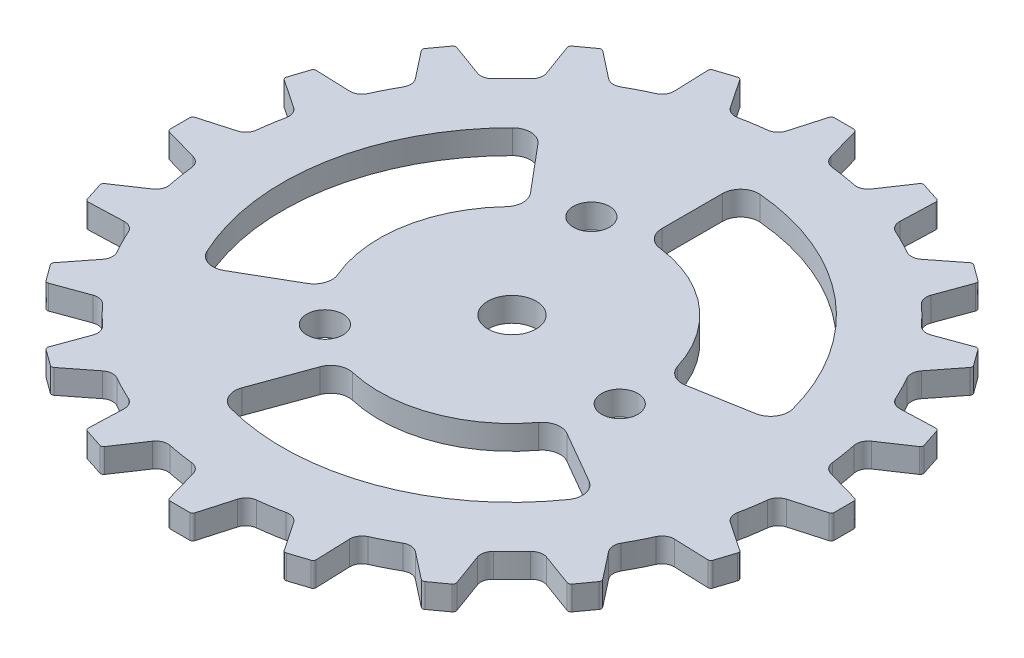
SolidWorks part; units mm, degrees
ref_plane "Front" through (0, 0, 0) normal (0, 0, 1) x (1, 0, 0)
ref_plane "Top" through (0, 0, 0) normal (0, 1, 0) x (1, 0, 0)
ref_plane "Right" through (0, 0, 0) normal (1, 0, 0) x (0, 0, -1)
sketch "草图1" plane through (0, 0, 0) normal (0, 1, 0) x (1, 0, 0)
  line L0 (-0.8114, 27.5) -> (0.8114, 27.5)
  line L3 (1.8377, 24.5681) -> (1.0518, 27.3187)
  line L7 (-1.8377, 24.5681) -> (-1.0518, 27.3187)
  line L8 (7.7263, 26.4048) -> (9.2697, 25.9033)
  line L9 (9.3397, 22.7977) -> (9.4423, 25.6566)
  line L10 (5.8442, 23.9335) -> (7.4416, 26.3066)
  line L11 (15.5076, 22.7249) -> (16.8206, 21.771)
  line L12 (15.9275, 18.7958) -> (16.9084, 21.483)
  line L13 (12.954, 20.9562) -> (15.2066, 22.7195)
  line L14 (21.771, 16.8206) -> (22.7249, 15.5076)
  line L15 (20.9562, 12.954) -> (22.7195, 15.2066)
  line L16 (18.7958, 15.9275) -> (21.483, 16.9084)
  line L17 (25.9033, 9.2697) -> (26.4048, 7.7263)
  line L18 (23.9335, 5.8442) -> (26.3066, 7.4416)
  line L19 (22.7977, 9.3397) -> (25.6566, 9.4423)
  line L20 (27.5, 0.8114) -> (27.5, -0.8114)
  line L21 (24.5681, -1.8377) -> (27.3187, -1.0518)
  line L22 (24.5681, 1.8377) -> (27.3187, 1.0518)
  line L23 (26.4048, -7.7263) -> (25.9033, -9.2697)
  line L24 (22.7977, -9.3397) -> (25.6566, -9.4423)
  line L25 (23.9335, -5.8442) -> (26.3066, -7.4416)
  line L26 (22.7249, -15.5076) -> (21.771, -16.8206)
  line L27 (18.7958, -15.9275) -> (21.483, -16.9084)
  line L28 (20.9562, -12.954) -> (22.7195, -15.2066)
  line L29 (16.8206, -21.771) -> (15.5076, -22.7249)
  line L30 (12.954, -20.9562) -> (15.2066, -22.7195)
  line L31 (15.9275, -18.7958) -> (16.9084, -21.483)
  line L32 (9.2697, -25.9033) -> (7.7263, -26.4048)
  line L33 (5.8442, -23.9335) -> (7.4416, -26.3066)
  line L34 (9.3397, -22.7977) -> (9.4423, -25.6566)
  line L35 (0.8114, -27.5) -> (-0.8114, -27.5)
  line L36 (-1.8377, -24.5681) -> (-1.0518, -27.3187)
  line L37 (1.8377, -24.5681) -> (1.0518, -27.3187)
  line L38 (-7.7263, -26.4048) -> (-9.2697, -25.9033)
  line L39 (-9.3397, -22.7977) -> (-9.4423, -25.6566)
  line L40 (-5.8442, -23.9335) -> (-7.4416, -26.3066)
  line L41 (-15.5076, -22.7249) -> (-16.8206, -21.771)
  line L42 (-15.9275, -18.7958) -> (-16.9084, -21.483)
  line L43 (-12.954, -20.9562) -> (-15.2066, -22.7195)
  line L44 (-21.771, -16.8206) -> (-22.7249, -15.5076)
  line L45 (-20.9562, -12.954) -> (-22.7195, -15.2066)
  line L46 (-18.7958, -15.9275) -> (-21.483, -16.9084)
  line L47 (-25.9033, -9.2697) -> (-26.4048, -7.7263)
  line L48 (-23.9335, -5.8442) -> (-26.3066, -7.4416)
  line L49 (-22.7977, -9.3397) -> (-25.6566, -9.4423)
  line L50 (-27.5, -0.8114) -> (-27.5, 0.8114)
  line L51 (-24.5681, 1.8377) -> (-27.3187, 1.0518)
  line L52 (-24.5681, -1.8377) -> (-27.3187, -1.0518)
  line L53 (-26.4048, 7.7263) -> (-25.9033, 9.2697)
  line L54 (-22.7977, 9.3397) -> (-25.6566, 9.4423)
  line L55 (-23.9335, 5.8442) -> (-26.3066, 7.4416)
  line L56 (-22.7249, 15.5076) -> (-21.771, 16.8206)
  line L57 (-18.7958, 15.9275) -> (-21.483, 16.9084)
  line L58 (-20.9562, 12.954) -> (-22.7195, 15.2066)
  line L59 (-16.8206, 21.771) -> (-15.5076, 22.7249)
  line L60 (-12.954, 20.9562) -> (-15.2066, 22.7195)
  line L61 (-15.9275, 18.7958) -> (-16.9084, 21.483)
  line L62 (-9.2697, 25.9033) -> (-7.7263, 26.4048)
  line L63 (-5.8442, 23.9335) -> (-7.4416, 26.3066)
  line L64 (-9.3397, 22.7977) -> (-9.4423, 25.6566)
  line L65 (0, 19) -> (0, 11)
  line L67 (18.7113, 3.2993) -> (10.8329, 1.9101)
  line L68 (16.4545, -9.5) -> (9.5263, -5.5)
  line L70 (-6.4984, -17.8542) -> (-3.7622, -10.3366)
  line L71 (-16.4545, -9.5) -> (-9.5263, -5.5)
  line L73 (-12.213, 14.5548) -> (-7.0707, 8.4265)
  line L74 (12.213, 14.5548) -> (7.0707, 8.4265) [skipped]
  line L75 (6.4984, -17.8542) -> (3.7622, -10.3366) [skipped]
  line L76 (-18.7113, 3.2993) -> (-10.8329, 1.9101) [skipped]
  arc A0 (-2.6872, 23.8491) -> (-4.814, 23.5122) centre (0, 0) ccw
  arc A2 (1.8377, 24.5681) -> (2.6872, 23.8491) centre (2.7992, 24.8428) ccw
  arc A3 (-1.8377, 24.5681) -> (-2.6872, 23.8491) centre (-2.7992, 24.8428) cw
  arc A4 (1.0518, 27.3187) -> (0.8114, 27.5) centre (0.8114, 27.25) ccw
  arc A5 (-1.0518, 27.3187) -> (-0.8114, 27.5) centre (-0.8114, 27.25) cw
  arc A6 (7.4416, 26.3066) -> (7.7263, 26.4048) centre (7.649, 26.167) cw
  arc A7 (9.4423, 25.6566) -> (9.2697, 25.9033) centre (9.1924, 25.6655) ccw
  arc A8 (5.8442, 23.9335) -> (4.814, 23.5122) centre (5.0146, 24.4919) cw
  arc A9 (9.3397, 22.7977) -> (9.9255, 21.8514) centre (10.3391, 22.7619) ccw
  arc A10 (15.2066, 22.7195) -> (15.5076, 22.7249) centre (15.3607, 22.5227) cw
  arc A11 (16.9084, 21.483) -> (16.8206, 21.771) centre (16.6736, 21.5688) ccw
  arc A12 (12.954, 20.9562) -> (11.8441, 20.8738) centre (12.3376, 21.7436) cw
  arc A13 (15.9275, 18.7958) -> (16.1922, 17.7148) centre (16.8668, 18.4529) ccw
  arc A14 (21.483, 16.9084) -> (21.771, 16.8206) centre (21.5688, 16.6736) cw
  arc A15 (22.7195, 15.2066) -> (22.7249, 15.5076) centre (22.5227, 15.3607) ccw
  arc A16 (18.7958, 15.9275) -> (17.7148, 16.1922) centre (18.4529, 16.8668) cw
  arc A17 (20.9562, 12.954) -> (20.8738, 11.8441) centre (21.7436, 12.3376) ccw
  arc A18 (25.6566, 9.4423) -> (25.9033, 9.2697) centre (25.6655, 9.1924) cw
  arc A19 (26.3066, 7.4416) -> (26.4048, 7.7263) centre (26.167, 7.649) ccw
  arc A20 (22.7977, 9.3397) -> (21.8514, 9.9255) centre (22.7619, 10.3391) cw
  arc A21 (23.9335, 5.8442) -> (23.5122, 4.814) centre (24.4919, 5.0146) ccw
  arc A22 (27.3187, 1.0518) -> (27.5, 0.8114) centre (27.25, 0.8114) cw
  arc A23 (27.3187, -1.0518) -> (27.5, -0.8114) centre (27.25, -0.8114) ccw
  arc A24 (24.5681, 1.8377) -> (23.8491, 2.6872) centre (24.8428, 2.7992) cw
  arc A25 (24.5681, -1.8377) -> (23.8491, -2.6872) centre (24.8428, -2.7992) ccw
  arc A26 (26.3066, -7.4416) -> (26.4048, -7.7263) centre (26.167, -7.649) cw
  arc A27 (25.6566, -9.4423) -> (25.9033, -9.2697) centre (25.6655, -9.1924) ccw
  arc A28 (23.9335, -5.8442) -> (23.5122, -4.814) centre (24.4919, -5.0146) cw
  arc A29 (22.7977, -9.3397) -> (21.8514, -9.9255) centre (22.7619, -10.3391) ccw
  arc A30 (22.7195, -15.2066) -> (22.7249, -15.5076) centre (22.5227, -15.3607) cw
  arc A31 (21.483, -16.9084) -> (21.771, -16.8206) centre (21.5688, -16.6736) ccw
  arc A32 (20.9562, -12.954) -> (20.8738, -11.8441) centre (21.7436, -12.3376) cw
  arc A33 (18.7958, -15.9275) -> (17.7148, -16.1922) centre (18.4529, -16.8668) ccw
  arc A34 (16.9084, -21.483) -> (16.8206, -21.771) centre (16.6736, -21.5688) cw
  arc A35 (15.2066, -22.7195) -> (15.5076, -22.7249) centre (15.3607, -22.5227) ccw
  arc A36 (15.9275, -18.7958) -> (16.1922, -17.7148) centre (16.8668, -18.4529) cw
  arc A37 (12.954, -20.9562) -> (11.8441, -20.8738) centre (12.3376, -21.7436) ccw
  arc A38 (9.4423, -25.6566) -> (9.2697, -25.9033) centre (9.1924, -25.6655) cw
  arc A39 (7.4416, -26.3066) -> (7.7263, -26.4048) centre (7.649, -26.167) ccw
  arc A40 (9.3397, -22.7977) -> (9.9255, -21.8514) centre (10.3391, -22.7619) cw
  arc A41 (5.8442, -23.9335) -> (4.814, -23.5122) centre (5.0146, -24.4919) ccw
  arc A42 (1.0518, -27.3187) -> (0.8114, -27.5) centre (0.8114, -27.25) cw
  arc A43 (-1.0518, -27.3187) -> (-0.8114, -27.5) centre (-0.8114, -27.25) ccw
  arc A44 (1.8377, -24.5681) -> (2.6872, -23.8491) centre (2.7992, -24.8428) cw
  arc A45 (-1.8377, -24.5681) -> (-2.6872, -23.8491) centre (-2.7992, -24.8428) ccw
  arc A46 (-7.4416, -26.3066) -> (-7.7263, -26.4048) centre (-7.649, -26.167) cw
  arc A47 (-9.4423, -25.6566) -> (-9.2697, -25.9033) centre (-9.1924, -25.6655) ccw
  arc A48 (-5.8442, -23.9335) -> (-4.814, -23.5122) centre (-5.0146, -24.4919) cw
  arc A49 (-9.3397, -22.7977) -> (-9.9255, -21.8514) centre (-10.3391, -22.7619) ccw
  arc A50 (-15.2066, -22.7195) -> (-15.5076, -22.7249) centre (-15.3607, -22.5227) cw
  arc A51 (-16.9084, -21.483) -> (-16.8206, -21.771) centre (-16.6736, -21.5688) ccw
  arc A52 (-12.954, -20.9562) -> (-11.8441, -20.8738) centre (-12.3376, -21.7436) cw
  arc A53 (-15.9275, -18.7958) -> (-16.1922, -17.7148) centre (-16.8668, -18.4529) ccw
  arc A54 (-21.483, -16.9084) -> (-21.771, -16.8206) centre (-21.5688, -16.6736) cw
  arc A55 (-22.7195, -15.2066) -> (-22.7249, -15.5076) centre (-22.5227, -15.3607) ccw
  arc A56 (-18.7958, -15.9275) -> (-17.7148, -16.1922) centre (-18.4529, -16.8668) cw
  arc A57 (-20.9562, -12.954) -> (-20.8738, -11.8441) centre (-21.7436, -12.3376) ccw
  arc A58 (-25.6566, -9.4423) -> (-25.9033, -9.2697) centre (-25.6655, -9.1924) cw
  arc A59 (-26.3066, -7.4416) -> (-26.4048, -7.7263) centre (-26.167, -7.649) ccw
  arc A60 (-22.7977, -9.3397) -> (-21.8514, -9.9255) centre (-22.7619, -10.3391) cw
  arc A61 (-23.9335, -5.8442) -> (-23.5122, -4.814) centre (-24.4919, -5.0146) ccw
  arc A62 (-27.3187, -1.0518) -> (-27.5, -0.8114) centre (-27.25, -0.8114) cw
  arc A63 (-27.3187, 1.0518) -> (-27.5, 0.8114) centre (-27.25, 0.8114) ccw
  arc A64 (-24.5681, -1.8377) -> (-23.8491, -2.6872) centre (-24.8428, -2.7992) cw
  arc A65 (-24.5681, 1.8377) -> (-23.8491, 2.6872) centre (-24.8428, 2.7992) ccw
  arc A66 (-26.3066, 7.4416) -> (-26.4048, 7.7263) centre (-26.167, 7.649) cw
  arc A67 (-25.6566, 9.4423) -> (-25.9033, 9.2697) centre (-25.6655, 9.1924) ccw
  arc A68 (-23.9335, 5.8442) -> (-23.5122, 4.814) centre (-24.4919, 5.0146) cw
  arc A69 (-22.7977, 9.3397) -> (-21.8514, 9.9255) centre (-22.7619, 10.3391) ccw
  arc A70 (-22.7195, 15.2066) -> (-22.7249, 15.5076) centre (-22.5227, 15.3607) cw
  arc A71 (-21.483, 16.9084) -> (-21.771, 16.8206) centre (-21.5688, 16.6736) ccw
  arc A72 (-20.9562, 12.954) -> (-20.8738, 11.8441) centre (-21.7436, 12.3376) cw
  arc A73 (-18.7958, 15.9275) -> (-17.7148, 16.1922) centre (-18.4529, 16.8668) ccw
  arc A74 (-16.9084, 21.483) -> (-16.8206, 21.771) centre (-16.6736, 21.5688) cw
  arc A75 (-15.2066, 22.7195) -> (-15.5076, 22.7249) centre (-15.3607, 22.5227) ccw
  arc A76 (-15.9275, 18.7958) -> (-16.1922, 17.7148) centre (-16.8668, 18.4529) cw
  arc A77 (-12.954, 20.9562) -> (-11.8441, 20.8738) centre (-12.3376, 21.7436) ccw
  arc A78 (-9.4423, 25.6566) -> (-9.2697, 25.9033) centre (-9.1924, 25.6655) cw
  arc A79 (-7.4416, 26.3066) -> (-7.7263, 26.4048) centre (-7.649, 26.167) ccw
  arc A80 (-9.3397, 22.7977) -> (-9.9255, 21.8514) centre (-10.3391, 22.7619) cw
  arc A81 (-5.8442, 23.9335) -> (-4.814, 23.5122) centre (-5.0146, 24.4919) ccw
  arc A82 (-9.9255, 21.8514) -> (-11.8441, 20.8738) centre (0, 0) ccw
  arc A83 (-16.1922, 17.7148) -> (-17.7148, 16.1922) centre (0, 0) ccw
  arc A84 (-20.8738, 11.8441) -> (-21.8514, 9.9255) centre (0, 0) ccw
  arc A85 (-23.5122, 4.814) -> (-23.8491, 2.6872) centre (0, 0) ccw
  arc A86 (-23.8491, -2.6872) -> (-23.5122, -4.814) centre (0, 0) ccw
  arc A87 (4.814, 23.5122) -> (2.6872, 23.8491) centre (0, 0) ccw
  arc A88 (11.8441, 20.8738) -> (9.9255, 21.8514) centre (0, 0) ccw
  arc A89 (17.7148, 16.1922) -> (16.1922, 17.7148) centre (0, 0) ccw
  arc A90 (21.8514, 9.9255) -> (20.8738, 11.8441) centre (0, 0) ccw
  arc A91 (23.8491, 2.6872) -> (23.5122, 4.814) centre (0, 0) ccw
  arc A92 (23.5122, -4.814) -> (23.8491, -2.6872) centre (0, 0) ccw
  arc A93 (20.8738, -11.8441) -> (21.8514, -9.9255) centre (0, 0) ccw
  arc A94 (16.1922, -17.7148) -> (17.7148, -16.1922) centre (0, 0) ccw
  arc A95 (9.9255, -21.8514) -> (11.8441, -20.8738) centre (0, 0) ccw
  arc A96 (-4.814, -23.5122) -> (-2.6872, -23.8491) centre (0, 0) ccw
  arc A97 (2.6872, -23.8491) -> (4.814, -23.5122) centre (0, 0) ccw
  arc A98 (-11.8441, -20.8738) -> (-9.9255, -21.8514) centre (0, 0) ccw
  arc A99 (-17.7148, -16.1922) -> (-16.1922, -17.7148) centre (0, 0) ccw
  arc A100 (-21.8514, -9.9255) -> (-20.8738, -11.8441) centre (0, 0) ccw
  arc A101 (-7.0707, 8.4265) -> (-9.5263, -5.5) centre (0, 0) ccw
  arc A102 (-12.213, 14.5548) -> (-16.4545, -9.5) centre (0, 0) ccw
  arc A103 (-6.4984, -17.8542) -> (16.4545, -9.5) centre (0, 0) ccw
  arc A104 (18.7113, 3.2993) -> (0, 19) centre (0, 0) ccw
  arc A105 (-3.7622, -10.3366) -> (9.5263, -5.5) centre (0, 0) ccw
  arc A106 (10.8329, 1.9101) -> (0, 11) centre (0, 0) ccw
  circle A107 centre (0, 0) radius 2
  circle A111 centre (-3.7622, 10.3366) radius 1.5
  circle A112 centre (10.8329, -1.9101) radius 1.5
  circle A113 centre (-7.0707, -8.4265) radius 1.5
  point P245 (0, 0)
  point P266 (0, 0)
  dimension "D1" = 20
  dimension "D2" = 9
extrude "凸台-拉伸1" add sketch "草图1" along normal blind 2
fillet "圆角1" radius 1.5 12 edges at (-3.7622, 1, 10.3366) (-6.4984, 1, 17.8542) (16.4545, 1, 9.5) (9.5263, 1, 5.5) (18.7113, 1, -3.2993) (10.8329, 1, -1.9101) (-12.213, 1, -14.5548) (-9.5263, 1, 5.5) (-7.0707, 1, -8.4265) (-16.4545, 1, 9.5) (0, 1, -11) (0, 1, -19)
